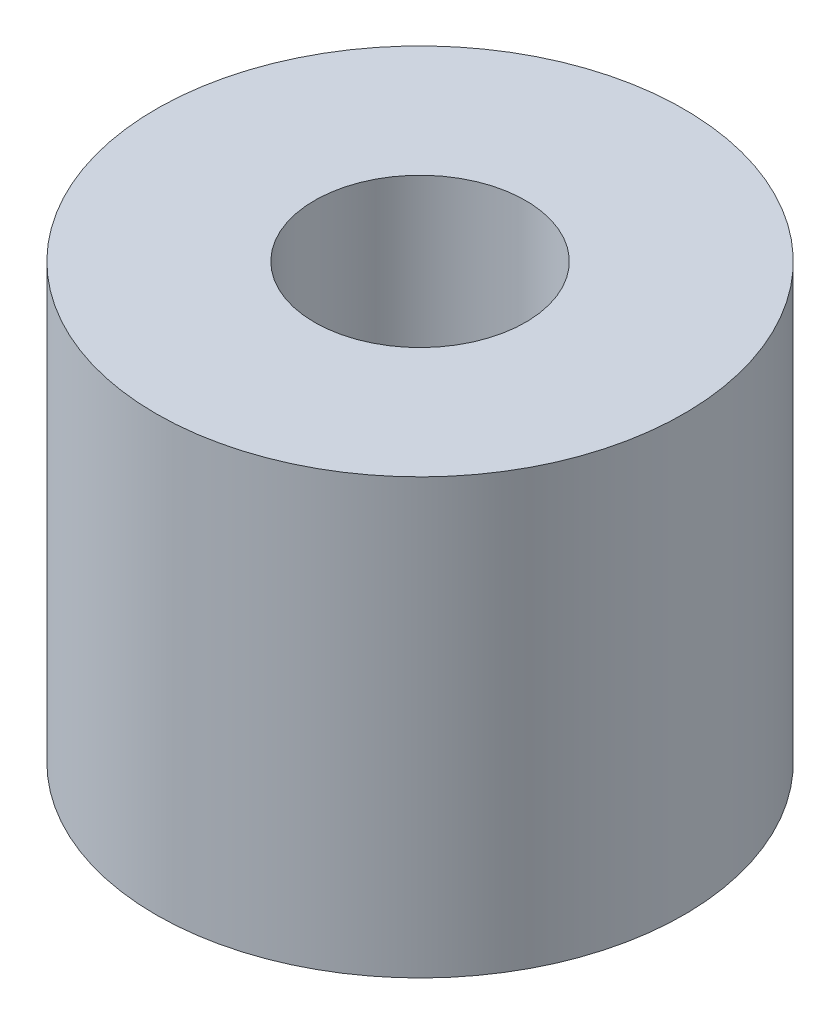
SolidWorks part; units mm, degrees
material "Plástico personalizado"
ref_plane "Alzado" through (0, 0, 0) normal (0, 0, 1) x (1, 0, 0)
ref_plane "Planta" through (0, 0, 0) normal (0, 1, 0) x (1, 0, 0)
ref_plane "Vista lateral" through (0, 0, 0) normal (1, 0, 0) x (0, 0, -1)
sketch "Croquis1" plane through (0, 0, 0) normal (0, 1, 0) x (1, 0, 0)
  circle A0 centre (0, 0) radius 2.25
  circle A1 centre (0, 0) radius 0.9
  dimension "D1" = 4.5
  dimension "D2" = 1.8
extrude "Saliente-Extruir1" add sketch "Croquis1" along normal blind 3.7
